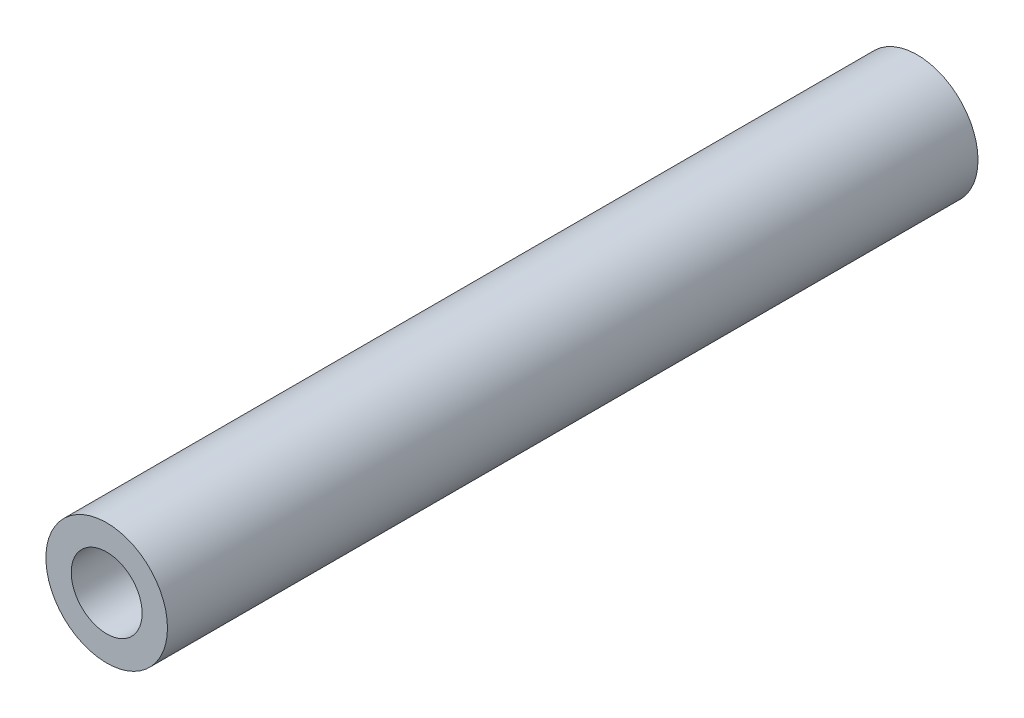
SolidWorks part; units mm, degrees
ref_plane "前视基准面" through (0, 0, 0) normal (0, 0, 1) x (1, 0, 0)
ref_plane "上视基准面" through (0, 0, 0) normal (0, 1, 0) x (1, 0, 0)
ref_plane "右视基准面" through (0, 0, 0) normal (1, 0, 0) x (0, 0, -1)
sketch "草图1" plane through (0, 0, 0) normal (0, 0, 1) x (1, 0, 0)
  circle A0 centre (0, 0) radius 1.75
  circle A1 centre (0, 0) radius 3
  dimension "D1" = 3.5
  dimension "D2" = 6
extrude "凸台-拉伸1" add sketch "草图1" along normal blind 40
